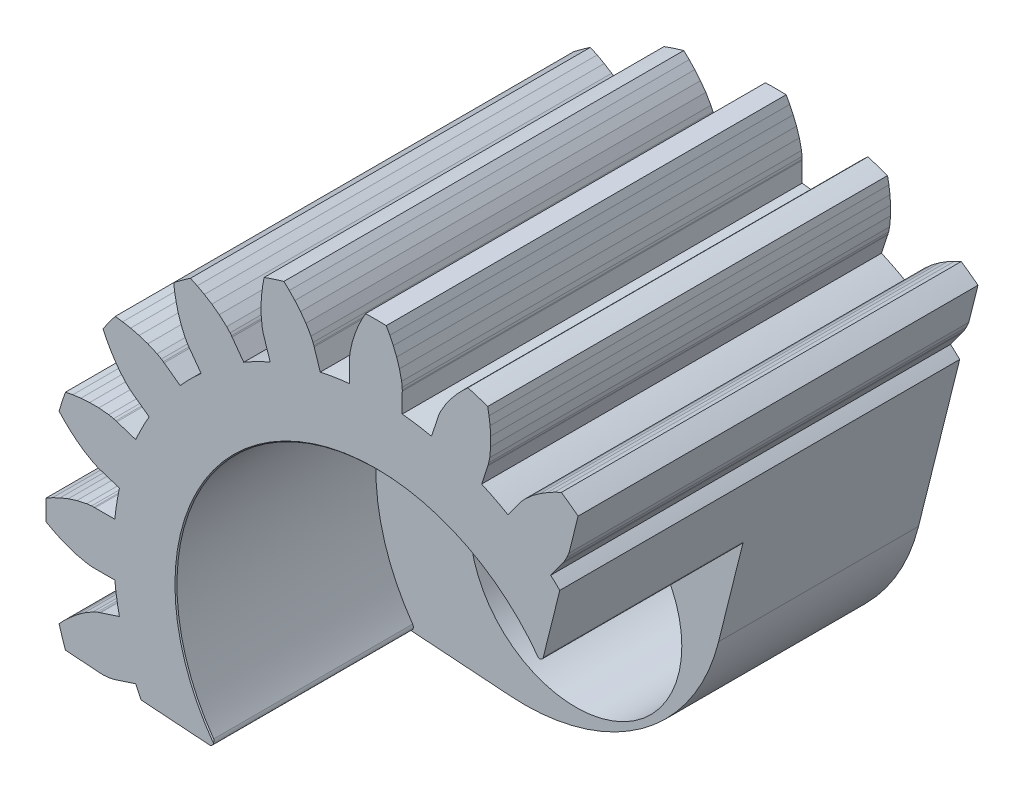
SolidWorks part; units mm, degrees
ref_plane "Plan de face" through (0, 0, 0) normal (0, 0, 1) x (1, 0, 0)
ref_plane "Plan de dessus" through (0, 0, 0) normal (0, 1, 0) x (1, 0, 0)
ref_plane "Plan de droite" through (0, 0, 0) normal (1, 0, 0) x (0, 0, -1)
ref_plane "Plan1" through (0, 0, 10) normal (0, 0, 1) x (1, 0, 0)
sketch "Esquisse1" plane through (0, 0, 10) normal (0, 0, 1) x (1, 0, 0)
  line L0 (7.794, 2.1657) -> (7.9224, 2.3017)
  line L1 (7.7623, 2.7945) -> (7.5784, 2.8291)
  line L2 (7.5784, 2.8291) -> (7.3779, 2.8553)
  line L3 (7.3779, 2.8553) -> (7.1581, 2.871)
  line L4 (7.1581, 2.871) -> (6.9289, 2.8707)
  line L5 (6.9289, 2.8707) -> (6.6791, 2.8463)
  line L6 (6.6791, 2.8463) -> (6.5582, 2.8219)
  line L7 (6.5582, 2.8219) -> (6.5007, 2.8057)
  line L8 (6.5007, 2.8057) -> (6.4762, 2.7971)
  line L9 (6.4762, 2.7971) -> (6.0062, 2.6442)
  line L10 (5.6696, 3.3049) -> (6.0695, 3.5952)
  line L11 (6.0695, 3.5952) -> (6.0908, 3.61)
  line L12 (6.0908, 3.61) -> (6.1378, 3.647)
  line L13 (6.1378, 3.647) -> (6.2286, 3.7305)
  line L14 (6.2286, 3.7305) -> (6.3951, 3.9182)
  line L15 (6.3951, 3.9182) -> (6.5301, 4.1035)
  line L16 (6.5301, 4.1035) -> (6.6466, 4.2905)
  line L17 (6.6466, 4.2905) -> (6.7433, 4.4681)
  line L18 (6.7433, 4.4681) -> (6.8234, 4.6372)
  line L19 (6.5188, 5.0564) -> (6.3332, 5.0325)
  line L20 (6.3332, 5.0325) -> (6.1345, 4.9955)
  line L21 (6.1345, 4.9955) -> (5.9206, 4.9424)
  line L22 (5.9206, 4.9424) -> (5.7027, 4.8713)
  line L23 (5.7027, 4.8713) -> (5.4727, 4.771)
  line L24 (5.4727, 4.771) -> (5.3652, 4.7104)
  line L25 (5.3652, 4.7104) -> (5.3155, 4.6772)
  line L26 (5.3155, 4.6772) -> (5.2948, 4.6615)
  line L27 (5.2948, 4.6615) -> (4.8952, 4.3708)
  line L28 (4.3708, 4.8952) -> (4.6615, 5.2948)
  line L29 (4.6615, 5.2948) -> (4.6772, 5.3155)
  line L30 (4.6772, 5.3155) -> (4.7104, 5.3652)
  line L31 (4.7104, 5.3652) -> (4.771, 5.4727)
  line L32 (4.771, 5.4727) -> (4.8713, 5.7027)
  line L33 (4.8713, 5.7027) -> (4.9424, 5.9206)
  line L34 (4.9424, 5.9206) -> (4.9955, 6.1345)
  line L35 (4.9955, 6.1345) -> (5.0325, 6.3332)
  line L36 (5.0325, 6.3332) -> (5.0564, 6.5188)
  line L37 (4.6372, 6.8234) -> (4.4681, 6.7433)
  line L38 (4.4681, 6.7433) -> (4.2905, 6.6466)
  line L39 (4.2905, 6.6466) -> (4.1035, 6.5301)
  line L40 (4.1035, 6.5301) -> (3.9182, 6.3951)
  line L41 (3.9182, 6.3951) -> (3.7305, 6.2286)
  line L42 (3.7305, 6.2286) -> (3.647, 6.1378)
  line L43 (3.647, 6.1378) -> (3.61, 6.0908)
  line L44 (3.61, 6.0908) -> (3.5952, 6.0695)
  line L45 (3.5952, 6.0695) -> (3.3049, 5.6696)
  line L46 (2.6442, 6.0062) -> (2.7971, 6.4762)
  line L47 (2.7971, 6.4762) -> (2.8057, 6.5007)
  line L48 (2.8057, 6.5007) -> (2.8219, 6.5582)
  line L49 (2.8219, 6.5582) -> (2.8463, 6.6791)
  line L50 (2.8463, 6.6791) -> (2.8707, 6.9289)
  line L51 (2.8707, 6.9289) -> (2.871, 7.1581)
  line L52 (2.871, 7.1581) -> (2.8553, 7.3779)
  line L53 (2.8553, 7.3779) -> (2.8291, 7.5784)
  line L54 (2.8291, 7.5784) -> (2.7945, 7.7623)
  line L55 (2.3017, 7.9224) -> (2.1657, 7.794)
  line L56 (2.1657, 7.794) -> (2.0266, 7.6472)
  line L57 (2.0266, 7.6472) -> (1.8848, 7.4786)
  line L58 (1.8848, 7.4786) -> (1.7502, 7.2929)
  line L59 (1.7502, 7.2929) -> (1.6232, 7.0765)
  line L60 (1.6232, 7.0765) -> (1.5718, 6.9644)
  line L61 (1.5718, 6.9644) -> (1.5512, 6.9083)
  line L62 (1.5512, 6.9083) -> (1.5437, 6.8834)
  line L63 (1.5437, 6.8834) -> (1.3912, 6.4133)
  line L64 (0.6587, 6.5294) -> (0.659, 7.0236)
  line L65 (0.659, 7.0236) -> (0.6595, 7.0495)
  line L66 (0.6595, 7.0495) -> (0.6572, 7.1092)
  line L67 (0.6572, 7.1092) -> (0.643, 7.2318)
  line L68 (0.643, 7.2318) -> (0.589, 7.4768)
  line L69 (0.589, 7.4768) -> (0.5185, 7.695)
  line L70 (0.5185, 7.695) -> (0.4357, 7.8992)
  line L71 (0.4357, 7.8992) -> (0.3488, 8.0817)
  line L72 (0.3488, 8.0817) -> (0.2591, 8.2459)
  line L73 (-0.2591, 8.2459) -> (-0.3488, 8.0817)
  line L74 (-0.3488, 8.0817) -> (-0.4357, 7.8992)
  line L75 (-0.4357, 7.8992) -> (-0.5185, 7.695)
  line L76 (-0.5185, 7.695) -> (-0.589, 7.4768)
  line L77 (-0.589, 7.4768) -> (-0.643, 7.2318)
  line L78 (-0.643, 7.2318) -> (-0.6572, 7.1092)
  line L79 (-0.6572, 7.1092) -> (-0.6595, 7.0495)
  line L80 (-0.6595, 7.0495) -> (-0.659, 7.0236)
  line L81 (-0.659, 7.0236) -> (-0.6587, 6.5294)
  line L82 (-1.3912, 6.4133) -> (-1.5437, 6.8834)
  line L83 (-1.5437, 6.8834) -> (-1.5512, 6.9083)
  line L84 (-1.5512, 6.9083) -> (-1.5718, 6.9644)
  line L85 (-1.5718, 6.9644) -> (-1.6232, 7.0765)
  line L86 (-1.6232, 7.0765) -> (-1.7502, 7.2929)
  line L87 (-1.7502, 7.2929) -> (-1.8848, 7.4786)
  line L88 (-1.8848, 7.4786) -> (-2.0266, 7.6472)
  line L89 (-2.0266, 7.6472) -> (-2.1657, 7.794)
  line L90 (-2.1657, 7.794) -> (-2.3017, 7.9224)
  line L91 (-2.7945, 7.7623) -> (-2.8291, 7.5784)
  line L92 (-2.8291, 7.5784) -> (-2.8553, 7.3779)
  line L93 (-2.8553, 7.3779) -> (-2.871, 7.1581)
  line L94 (-2.871, 7.1581) -> (-2.8707, 6.9289)
  line L95 (-2.8707, 6.9289) -> (-2.8463, 6.6791)
  line L96 (-2.8463, 6.6791) -> (-2.8219, 6.5582)
  line L97 (-2.8219, 6.5582) -> (-2.8057, 6.5007)
  line L98 (-2.8057, 6.5007) -> (-2.7971, 6.4762)
  line L99 (-2.7971, 6.4762) -> (-2.6442, 6.0062)
  line L100 (-3.3049, 5.6696) -> (-3.5952, 6.0695)
  line L101 (-3.5952, 6.0695) -> (-3.61, 6.0908)
  line L102 (-3.61, 6.0908) -> (-3.647, 6.1378)
  line L103 (-3.647, 6.1378) -> (-3.7305, 6.2286)
  line L104 (-3.7305, 6.2286) -> (-3.9182, 6.3951)
  line L105 (-3.9182, 6.3951) -> (-4.1035, 6.5301)
  line L106 (-4.1035, 6.5301) -> (-4.2905, 6.6466)
  line L107 (-4.2905, 6.6466) -> (-4.4681, 6.7433)
  line L108 (-4.4681, 6.7433) -> (-4.6372, 6.8234)
  line L109 (-5.0564, 6.5188) -> (-5.0325, 6.3332)
  line L110 (-5.0325, 6.3332) -> (-4.9955, 6.1345)
  line L111 (-4.9955, 6.1345) -> (-4.9424, 5.9206)
  line L112 (-4.9424, 5.9206) -> (-4.8713, 5.7027)
  line L113 (-4.8713, 5.7027) -> (-4.771, 5.4727)
  line L114 (-4.771, 5.4727) -> (-4.7104, 5.3652)
  line L115 (-4.7104, 5.3652) -> (-4.6772, 5.3155)
  line L116 (-4.6772, 5.3155) -> (-4.6615, 5.2948)
  line L117 (-4.6615, 5.2948) -> (-4.3708, 4.8952)
  line L118 (-4.8952, 4.3708) -> (-5.2948, 4.6615)
  line L119 (-5.2948, 4.6615) -> (-5.3155, 4.6772)
  line L120 (-5.3155, 4.6772) -> (-5.3652, 4.7104)
  line L121 (-5.3652, 4.7104) -> (-5.4727, 4.771)
  line L122 (-5.4727, 4.771) -> (-5.7027, 4.8713)
  line L123 (-5.7027, 4.8713) -> (-5.9206, 4.9424)
  line L124 (-5.9206, 4.9424) -> (-6.1345, 4.9955)
  line L125 (-6.1345, 4.9955) -> (-6.3332, 5.0325)
  line L126 (-6.3332, 5.0325) -> (-6.5188, 5.0564)
  line L127 (-6.8234, 4.6372) -> (-6.7433, 4.4681)
  line L128 (-6.7433, 4.4681) -> (-6.6466, 4.2905)
  line L129 (-6.6466, 4.2905) -> (-6.5301, 4.1035)
  line L130 (-6.5301, 4.1035) -> (-6.3951, 3.9182)
  line L131 (-6.3951, 3.9182) -> (-6.2286, 3.7305)
  line L132 (-6.2286, 3.7305) -> (-6.1378, 3.647)
  line L133 (-6.1378, 3.647) -> (-6.0908, 3.61)
  line L134 (-6.0908, 3.61) -> (-6.0695, 3.5952)
  line L135 (-6.0695, 3.5952) -> (-5.6696, 3.3049)
  line L136 (-6.0062, 2.6442) -> (-6.4762, 2.7971)
  line L137 (-6.4762, 2.7971) -> (-6.5007, 2.8057)
  line L138 (-6.5007, 2.8057) -> (-6.5582, 2.8219)
  line L139 (-6.5582, 2.8219) -> (-6.6791, 2.8463)
  line L140 (-6.6791, 2.8463) -> (-6.9289, 2.8707)
  line L141 (-6.9289, 2.8707) -> (-7.1581, 2.871)
  line L142 (-7.1581, 2.871) -> (-7.3779, 2.8553)
  line L143 (-7.3779, 2.8553) -> (-7.5784, 2.8291)
  line L144 (-7.5784, 2.8291) -> (-7.7623, 2.7945)
  line L145 (-7.9224, 2.3017) -> (-7.794, 2.1657)
  line L146 (-7.794, 2.1657) -> (-7.6472, 2.0266)
  line L147 (-7.6472, 2.0266) -> (-7.4786, 1.8848)
  line L148 (-7.4786, 1.8848) -> (-7.2929, 1.7502)
  line L149 (-7.2929, 1.7502) -> (-7.0765, 1.6232)
  line L150 (-7.0765, 1.6232) -> (-6.9644, 1.5718)
  line L151 (-6.9644, 1.5718) -> (-6.9083, 1.5512)
  line L152 (-6.9083, 1.5512) -> (-6.8834, 1.5437)
  line L153 (-6.8834, 1.5437) -> (-6.4133, 1.3912)
  line L154 (-6.5294, 0.6587) -> (-7.0236, 0.659)
  line L155 (-7.0236, 0.659) -> (-7.0495, 0.6595)
  line L156 (-7.0495, 0.6595) -> (-7.1092, 0.6572)
  line L157 (-7.1092, 0.6572) -> (-7.2318, 0.643)
  line L158 (-7.2318, 0.643) -> (-7.4768, 0.589)
  line L159 (-7.4768, 0.589) -> (-7.695, 0.5185)
  line L160 (-7.695, 0.5185) -> (-7.8992, 0.4357)
  line L161 (-7.8992, 0.4357) -> (-8.0817, 0.3488)
  line L162 (-8.0817, 0.3488) -> (-8.2459, 0.2591)
  line L163 (-8.2459, -0.2591) -> (-8.0817, -0.3488)
  line L164 (-8.0817, -0.3488) -> (-7.8992, -0.4357)
  line L165 (-7.8992, -0.4357) -> (-7.695, -0.5185)
  line L166 (-7.695, -0.5185) -> (-7.4768, -0.589)
  line L167 (-7.4768, -0.589) -> (-7.2318, -0.643)
  line L168 (-7.2318, -0.643) -> (-7.1092, -0.6572)
  line L169 (-7.1092, -0.6572) -> (-7.0495, -0.6595)
  line L170 (-7.0495, -0.6595) -> (-7.0236, -0.659)
  line L171 (-7.0236, -0.659) -> (-6.5294, -0.6587)
  line L172 (-6.4133, -1.3912) -> (-6.8834, -1.5437)
  line L173 (-6.8834, -1.5437) -> (-6.9083, -1.5512)
  line L174 (-6.9083, -1.5512) -> (-6.9644, -1.5718)
  line L175 (-6.9644, -1.5718) -> (-7.0765, -1.6232)
  line L176 (-7.0765, -1.6232) -> (-7.2929, -1.7502)
  line L177 (-7.2929, -1.7502) -> (-7.4786, -1.8848)
  line L178 (-7.4786, -1.8848) -> (-7.6472, -2.0266)
  line L179 (-7.6472, -2.0266) -> (-7.794, -2.1657)
  line L180 (-7.794, -2.1657) -> (-7.9224, -2.3017)
  line L181 (-7.7623, -2.7945) -> (-7.5784, -2.8291)
  line L182 (-7.5784, -2.8291) -> (-7.3779, -2.8553)
  line L183 (-7.3779, -2.8553) -> (-7.1581, -2.871)
  line L184 (-7.1581, -2.871) -> (-6.9289, -2.8707)
  line L185 (-6.9289, -2.8707) -> (-6.6791, -2.8463)
  line L186 (-6.6791, -2.8463) -> (-6.5582, -2.8219)
  line L187 (-6.5582, -2.8219) -> (-6.5007, -2.8057)
  line L188 (-6.5007, -2.8057) -> (-6.4762, -2.7971)
  line L189 (-6.4762, -2.7971) -> (-6.0062, -2.6442)
  line L190 (-5.6696, -3.3049) -> (-6.0695, -3.5952)
  line L191 (-6.0695, -3.5952) -> (-6.0908, -3.61)
  line L192 (-6.0908, -3.61) -> (-6.1378, -3.647)
  line L193 (-6.1378, -3.647) -> (-6.2286, -3.7305)
  line L194 (-6.2286, -3.7305) -> (-6.3951, -3.9182)
  line L195 (-6.3951, -3.9182) -> (-6.5301, -4.1035)
  line L196 (-6.5301, -4.1035) -> (-6.6466, -4.2905)
  line L197 (-6.6466, -4.2905) -> (-6.7433, -4.4681)
  line L198 (-6.7433, -4.4681) -> (-6.8234, -4.6372)
  line L199 (-6.5188, -5.0564) -> (-6.3332, -5.0325)
  line L200 (-6.3332, -5.0325) -> (-6.1345, -4.9955)
  line L201 (-6.1345, -4.9955) -> (-5.9206, -4.9424)
  line L202 (-5.9206, -4.9424) -> (-5.7027, -4.8713)
  line L203 (-5.7027, -4.8713) -> (-5.4727, -4.771)
  line L204 (-5.4727, -4.771) -> (-5.3652, -4.7104)
  line L205 (-5.3652, -4.7104) -> (-5.3155, -4.6772)
  line L206 (-5.3155, -4.6772) -> (-5.2948, -4.6615)
  line L207 (-5.2948, -4.6615) -> (-4.8952, -4.3708)
  line L208 (-4.3708, -4.8952) -> (-4.6615, -5.2948)
  line L209 (-4.6615, -5.2948) -> (-4.6772, -5.3155)
  line L210 (-4.6772, -5.3155) -> (-4.7104, -5.3652)
  line L211 (-4.7104, -5.3652) -> (-4.771, -5.4727)
  line L212 (-4.771, -5.4727) -> (-4.8713, -5.7027)
  line L213 (-4.8713, -5.7027) -> (-4.9424, -5.9206)
  line L214 (-4.9424, -5.9206) -> (-4.9955, -6.1345)
  line L215 (-4.9955, -6.1345) -> (-5.0325, -6.3332)
  line L216 (-5.0325, -6.3332) -> (-5.0564, -6.5188)
  line L217 (-4.6372, -6.8234) -> (-4.4681, -6.7433)
  line L218 (-4.4681, -6.7433) -> (-4.2905, -6.6466)
  line L219 (-4.2905, -6.6466) -> (-4.1035, -6.5301)
  line L220 (-4.1035, -6.5301) -> (-3.9182, -6.3951)
  line L221 (-3.9182, -6.3951) -> (-3.7305, -6.2286)
  line L222 (-3.7305, -6.2286) -> (-3.647, -6.1378)
  line L223 (-3.647, -6.1378) -> (-3.61, -6.0908)
  line L224 (-3.61, -6.0908) -> (-3.5952, -6.0695)
  line L225 (-3.5952, -6.0695) -> (-3.3049, -5.6696)
  line L226 (-2.6442, -6.0062) -> (-2.7971, -6.4762)
  line L227 (-2.7971, -6.4762) -> (-2.8057, -6.5007)
  line L228 (-2.8057, -6.5007) -> (-2.8219, -6.5582)
  line L229 (-2.8219, -6.5582) -> (-2.8463, -6.6791)
  line L230 (-2.8463, -6.6791) -> (-2.8707, -6.9289)
  line L231 (-2.8707, -6.9289) -> (-2.871, -7.1581)
  line L232 (-2.871, -7.1581) -> (-2.8553, -7.3779)
  line L233 (-2.8553, -7.3779) -> (-2.8291, -7.5784)
  line L234 (-2.8291, -7.5784) -> (-2.7945, -7.7623)
  line L235 (-2.3017, -7.9224) -> (-2.1657, -7.794)
  line L236 (-2.1657, -7.794) -> (-2.0266, -7.6472)
  line L237 (-2.0266, -7.6472) -> (-1.8848, -7.4786)
  line L238 (-1.8848, -7.4786) -> (-1.7502, -7.2929)
  line L239 (-1.7502, -7.2929) -> (-1.6232, -7.0765)
  line L240 (-1.6232, -7.0765) -> (-1.5718, -6.9644)
  line L241 (-1.5718, -6.9644) -> (-1.5512, -6.9083)
  line L242 (-1.5512, -6.9083) -> (-1.5437, -6.8834)
  line L243 (-1.5437, -6.8834) -> (-1.3912, -6.4133)
  line L244 (-0.6587, -6.5294) -> (-0.659, -7.0236)
  line L245 (-0.659, -7.0236) -> (-0.6595, -7.0495)
  line L246 (-0.6595, -7.0495) -> (-0.6572, -7.1092)
  line L247 (-0.6572, -7.1092) -> (-0.643, -7.2318)
  line L248 (-0.643, -7.2318) -> (-0.589, -7.4768)
  line L249 (-0.589, -7.4768) -> (-0.5185, -7.695)
  line L250 (-0.5185, -7.695) -> (-0.4357, -7.8992)
  line L251 (-0.4357, -7.8992) -> (-0.3488, -8.0817)
  line L252 (-0.3488, -8.0817) -> (-0.2591, -8.2459)
  line L253 (0.2591, -8.2459) -> (0.3488, -8.0817)
  line L254 (0.3488, -8.0817) -> (0.4357, -7.8992)
  line L255 (0.4357, -7.8992) -> (0.5185, -7.695)
  line L256 (0.5185, -7.695) -> (0.589, -7.4768)
  line L257 (0.589, -7.4768) -> (0.643, -7.2318)
  line L258 (0.643, -7.2318) -> (0.6572, -7.1092)
  line L259 (0.6572, -7.1092) -> (0.6595, -7.0495)
  line L260 (0.6595, -7.0495) -> (0.659, -7.0236)
  line L261 (0.659, -7.0236) -> (0.6587, -6.5294)
  line L262 (1.3912, -6.4133) -> (1.5437, -6.8834)
  line L263 (1.5437, -6.8834) -> (1.5512, -6.9083)
  line L264 (1.5512, -6.9083) -> (1.5718, -6.9644)
  line L265 (1.5718, -6.9644) -> (1.6232, -7.0765)
  line L266 (1.6232, -7.0765) -> (1.7502, -7.2929)
  line L267 (1.7502, -7.2929) -> (1.8848, -7.4786)
  line L268 (1.8848, -7.4786) -> (2.0266, -7.6472)
  line L269 (2.0266, -7.6472) -> (2.1657, -7.794)
  line L270 (2.1657, -7.794) -> (2.3017, -7.9224)
  line L271 (2.7945, -7.7623) -> (2.8291, -7.5784)
  line L272 (2.8291, -7.5784) -> (2.8553, -7.3779)
  line L273 (2.8553, -7.3779) -> (2.871, -7.1581)
  line L274 (2.871, -7.1581) -> (2.8707, -6.9289)
  line L275 (2.8707, -6.9289) -> (2.8463, -6.6791)
  line L276 (2.8463, -6.6791) -> (2.8219, -6.5582)
  line L277 (2.8219, -6.5582) -> (2.8057, -6.5007)
  line L278 (2.8057, -6.5007) -> (2.7971, -6.4762)
  line L279 (2.7971, -6.4762) -> (2.6442, -6.0062)
  line L280 (3.3049, -5.6696) -> (3.5952, -6.0695)
  line L281 (3.5952, -6.0695) -> (3.61, -6.0908)
  line L282 (3.61, -6.0908) -> (3.647, -6.1378)
  line L283 (3.647, -6.1378) -> (3.7305, -6.2286)
  line L284 (3.7305, -6.2286) -> (3.9182, -6.3951)
  line L285 (3.9182, -6.3951) -> (4.1035, -6.5301)
  line L286 (4.1035, -6.5301) -> (4.2905, -6.6466)
  line L287 (4.2905, -6.6466) -> (4.4681, -6.7433)
  line L288 (4.4681, -6.7433) -> (4.6372, -6.8234)
  line L289 (5.0564, -6.5188) -> (5.0325, -6.3332)
  line L290 (5.0325, -6.3332) -> (4.9955, -6.1345)
  line L291 (4.9955, -6.1345) -> (4.9424, -5.9206)
  line L292 (4.9424, -5.9206) -> (4.8713, -5.7027)
  line L293 (4.8713, -5.7027) -> (4.771, -5.4727)
  line L294 (4.771, -5.4727) -> (4.7104, -5.3652)
  line L295 (4.7104, -5.3652) -> (4.6772, -5.3155)
  line L296 (4.6772, -5.3155) -> (4.6615, -5.2948)
  line L297 (4.6615, -5.2948) -> (4.3708, -4.8952)
  line L298 (4.8952, -4.3708) -> (5.2948, -4.6615)
  line L299 (5.2948, -4.6615) -> (5.3155, -4.6772)
  line L300 (5.3155, -4.6772) -> (5.3652, -4.7104)
  line L301 (5.3652, -4.7104) -> (5.4727, -4.771)
  line L302 (5.4727, -4.771) -> (5.7027, -4.8713)
  line L303 (5.7027, -4.8713) -> (5.9206, -4.9424)
  line L304 (5.9206, -4.9424) -> (6.1345, -4.9955)
  line L305 (6.1345, -4.9955) -> (6.3332, -5.0325)
  line L306 (6.3332, -5.0325) -> (6.5188, -5.0564)
  line L307 (6.8234, -4.6372) -> (6.7433, -4.4681)
  line L308 (6.7433, -4.4681) -> (6.6466, -4.2905)
  line L309 (6.6466, -4.2905) -> (6.5301, -4.1035)
  line L310 (6.5301, -4.1035) -> (6.3951, -3.9182)
  line L311 (6.3951, -3.9182) -> (6.2286, -3.7305)
  line L312 (6.2286, -3.7305) -> (6.1378, -3.647)
  line L313 (6.1378, -3.647) -> (6.0908, -3.61)
  line L314 (6.0908, -3.61) -> (6.0695, -3.5952)
  line L315 (6.0695, -3.5952) -> (5.6696, -3.3049)
  line L316 (6.0062, -2.6442) -> (6.4762, -2.7971)
  line L317 (6.4762, -2.7971) -> (6.5007, -2.8057)
  line L318 (6.5007, -2.8057) -> (6.5582, -2.8219)
  line L319 (6.5582, -2.8219) -> (6.6791, -2.8463)
  line L320 (6.6791, -2.8463) -> (6.9289, -2.8707)
  line L321 (6.9289, -2.8707) -> (7.1581, -2.871)
  line L322 (7.1581, -2.871) -> (7.3779, -2.8553)
  line L323 (7.3779, -2.8553) -> (7.5784, -2.8291)
  line L324 (7.5784, -2.8291) -> (7.7623, -2.7945)
  line L325 (7.9224, -2.3017) -> (7.794, -2.1657)
  line L326 (7.794, -2.1657) -> (7.6472, -2.0266)
  line L327 (7.6472, -2.0266) -> (7.4786, -1.8848)
  line L328 (7.4786, -1.8848) -> (7.2929, -1.7502)
  line L329 (7.2929, -1.7502) -> (7.0765, -1.6232)
  line L330 (7.0765, -1.6232) -> (6.9644, -1.5718)
  line L331 (6.9644, -1.5718) -> (6.9083, -1.5512)
  line L332 (6.9083, -1.5512) -> (6.8834, -1.5437)
  line L333 (6.8834, -1.5437) -> (6.4133, -1.3912)
  line L334 (6.5294, -0.6587) -> (7.0236, -0.659)
  line L335 (7.0236, -0.659) -> (7.0495, -0.6595)
  line L336 (7.0495, -0.6595) -> (7.1092, -0.6572)
  line L337 (7.1092, -0.6572) -> (7.2318, -0.643)
  line L338 (7.2318, -0.643) -> (7.4768, -0.589)
  line L339 (7.4768, -0.589) -> (7.695, -0.5185)
  line L340 (7.695, -0.5185) -> (7.8992, -0.4357)
  line L341 (7.8992, -0.4357) -> (8.0817, -0.3488)
  line L342 (8.0817, -0.3488) -> (8.2459, -0.2591)
  line L343 (8.2459, 0.2591) -> (8.0817, 0.3488)
  line L344 (8.0817, 0.3488) -> (7.8992, 0.4357)
  line L345 (7.8992, 0.4357) -> (7.695, 0.5185)
  line L346 (7.695, 0.5185) -> (7.4768, 0.589)
  line L347 (7.4768, 0.589) -> (7.2318, 0.643)
  line L348 (7.2318, 0.643) -> (7.1092, 0.6572)
  line L349 (7.1092, 0.6572) -> (7.0495, 0.6595)
  line L350 (7.0495, 0.6595) -> (7.0236, 0.659)
  line L351 (7.0236, 0.659) -> (6.5294, 0.6587)
  line L352 (6.4133, 1.3912) -> (6.8834, 1.5437)
  line L353 (6.8834, 1.5437) -> (6.9083, 1.5512)
  line L354 (6.9083, 1.5512) -> (6.9644, 1.5718)
  line L355 (6.9644, 1.5718) -> (7.0765, 1.6232)
  line L356 (7.0765, 1.6232) -> (7.2929, 1.7502)
  line L357 (7.2929, 1.7502) -> (7.4786, 1.8848)
  line L358 (7.4786, 1.8848) -> (7.6472, 2.0266)
  line L359 (7.6472, 2.0266) -> (7.794, 2.1657)
  circle A0 centre (0, 0) radius 2.5
  arc A1 (7.9224, 2.3017) -> (7.7623, 2.7945) centre (0, 0) ccw
  arc A2 (6.0062, 2.6442) -> (5.6696, 3.3049) centre (0, 0) ccw
  arc A3 (6.8234, 4.6372) -> (6.5188, 5.0564) centre (0, 0) ccw
  arc A4 (4.8952, 4.3708) -> (4.3708, 4.8952) centre (0, 0) ccw
  arc A5 (5.0564, 6.5188) -> (4.6372, 6.8234) centre (0, 0) ccw
  arc A6 (3.3049, 5.6696) -> (2.6442, 6.0062) centre (0, 0) ccw
  arc A7 (2.7945, 7.7623) -> (2.3017, 7.9224) centre (0, 0) ccw
  arc A8 (1.3912, 6.4133) -> (0.6587, 6.5294) centre (0, 0) ccw
  arc A9 (0.2591, 8.2459) -> (-0.2591, 8.2459) centre (0, 0) ccw
  arc A10 (-0.6587, 6.5294) -> (-1.3912, 6.4133) centre (0, 0) ccw
  arc A11 (-2.3017, 7.9224) -> (-2.7945, 7.7623) centre (0, 0) ccw
  arc A12 (-2.6442, 6.0062) -> (-3.3049, 5.6696) centre (0, 0) ccw
  arc A13 (-4.6372, 6.8234) -> (-5.0564, 6.5188) centre (0, 0) ccw
  arc A14 (-4.3708, 4.8952) -> (-4.8952, 4.3708) centre (0, 0) ccw
  arc A15 (-6.5188, 5.0564) -> (-6.8234, 4.6372) centre (0, 0) ccw
  arc A16 (-5.6696, 3.3049) -> (-6.0062, 2.6442) centre (0, 0) ccw
  arc A17 (-7.7623, 2.7945) -> (-7.9224, 2.3017) centre (0, 0) ccw
  arc A18 (-6.4133, 1.3912) -> (-6.5294, 0.6587) centre (0, 0) ccw
  arc A19 (-8.2459, 0.2591) -> (-8.2459, -0.2591) centre (0, 0) ccw
  arc A20 (-6.5294, -0.6587) -> (-6.4133, -1.3912) centre (0, 0) ccw
  arc A21 (-7.9224, -2.3017) -> (-7.7623, -2.7945) centre (0, 0) ccw
  arc A22 (-6.0062, -2.6442) -> (-5.6696, -3.3049) centre (0, 0) ccw
  arc A23 (-6.8234, -4.6372) -> (-6.5188, -5.0564) centre (0, 0) ccw
  arc A24 (-4.8952, -4.3708) -> (-4.3708, -4.8952) centre (0, 0) ccw
  arc A25 (-5.0564, -6.5188) -> (-4.6372, -6.8234) centre (0, 0) ccw
  arc A26 (-3.3049, -5.6696) -> (-2.6442, -6.0062) centre (0, 0) ccw
  arc A27 (-2.7945, -7.7623) -> (-2.3017, -7.9224) centre (0, 0) ccw
  arc A28 (-1.3912, -6.4133) -> (-0.6587, -6.5294) centre (0, 0) ccw
  arc A29 (-0.2591, -8.2459) -> (0.2591, -8.2459) centre (0, 0) ccw
  arc A30 (0.6587, -6.5294) -> (1.3912, -6.4133) centre (0, 0) ccw
  arc A31 (2.3017, -7.9224) -> (2.7945, -7.7623) centre (0, 0) ccw
  arc A32 (2.6442, -6.0062) -> (3.3049, -5.6696) centre (0, 0) ccw
  arc A33 (4.6372, -6.8234) -> (5.0564, -6.5188) centre (0, 0) ccw
  arc A34 (4.3708, -4.8952) -> (4.8952, -4.3708) centre (0, 0) ccw
  arc A35 (6.5188, -5.0564) -> (6.8234, -4.6372) centre (0, 0) ccw
  arc A36 (5.6696, -3.3049) -> (6.0062, -2.6442) centre (0, 0) ccw
  arc A37 (7.7623, -2.7945) -> (7.9224, -2.3017) centre (0, 0) ccw
  arc A38 (6.4133, -1.3912) -> (6.5294, -0.6587) centre (0, 0) ccw
  arc A39 (8.2459, -0.2591) -> (8.2459, 0.2591) centre (0, 0) ccw
  arc A40 (6.5294, 0.6587) -> (6.4133, 1.3912) centre (0, 0) ccw
extrude "Boss.-Extru.1" add sketch "Esquisse1" against normal blind 10
hole_wizard "Chambrage pour vis à tête cylindrique à 6 pans creux (ou vis CHC) M51" positions "Esquisse3" profile "Esquisse2" counterbore size "M5" standard "Ansi Metric" end condition through all
sketch "Esquisse3" plane through (0, 0, 10) normal (0, 0, 1) x (1, 0, 0)
  point P1 (0, 0)
sketch "Esquisse2" plane through (0, 0, 10) normal (1, 0, 0) x (0, -1, 0)
  line L0 (0, 0) -> (0, 10)
  line L1 (0, 10) -> (2.65, 10)
  line L3 (2.65, 10) -> (2.65, 5)
  line L4 (5, 5) -> (2.65, 5)
  line L5 (5, 5) -> (5, 0.025)
  line L6 (5, 0.025) -> (5.025, 0)
  line L7 (5.025, 0) -> (0, 0)
  line L8 (-5, 0.025) -> (-5.025, 0) construction
  line L11 (0, -6.35) -> (0, 107.95) construction
  dimension "Diamètre du perçage jusqu'au prochain" = 5.3
  dimension "Profondeur du perçage jusqu'au prochain" = 10
  dimension "Diamètre du chambrage" = 10
  dimension "Profondeur du chambrage" = 5
  dimension "Diamètre du fraisage entrant" = 10.05
  dimension "Angle du fraisage entrant" = 90
sketch "Esquisse4" plane through (0, 0, 10) normal (0, 0, 1) x (1, 0, 0)
  line L2 (5.0564, 6.5188) -> (3.5695, 0.5549)
  line L3 (-7.7623, -2.7945) -> (-1.6308, -3.2233)
  arc A5 (-7.7623, -2.7945) -> (5.0564, 6.5188) centre (0, 0) ccw
  arc A6 (-1.6308, -3.2233) -> (3.5695, 0.5549) centre (-1.282, 1.7645) ccw
  dimension "D2" = 5
  dimension "D1" = 100
extrude "Enlèv. mat.-Extru.1" cut sketch "Esquisse4" against normal through all
fillet "Congé1" radius 0.1 2 edges at (4.1328, 2.8143, 7.4875) (-3.9536, -3.0609, 7.4875)
ref_point "Point1"
